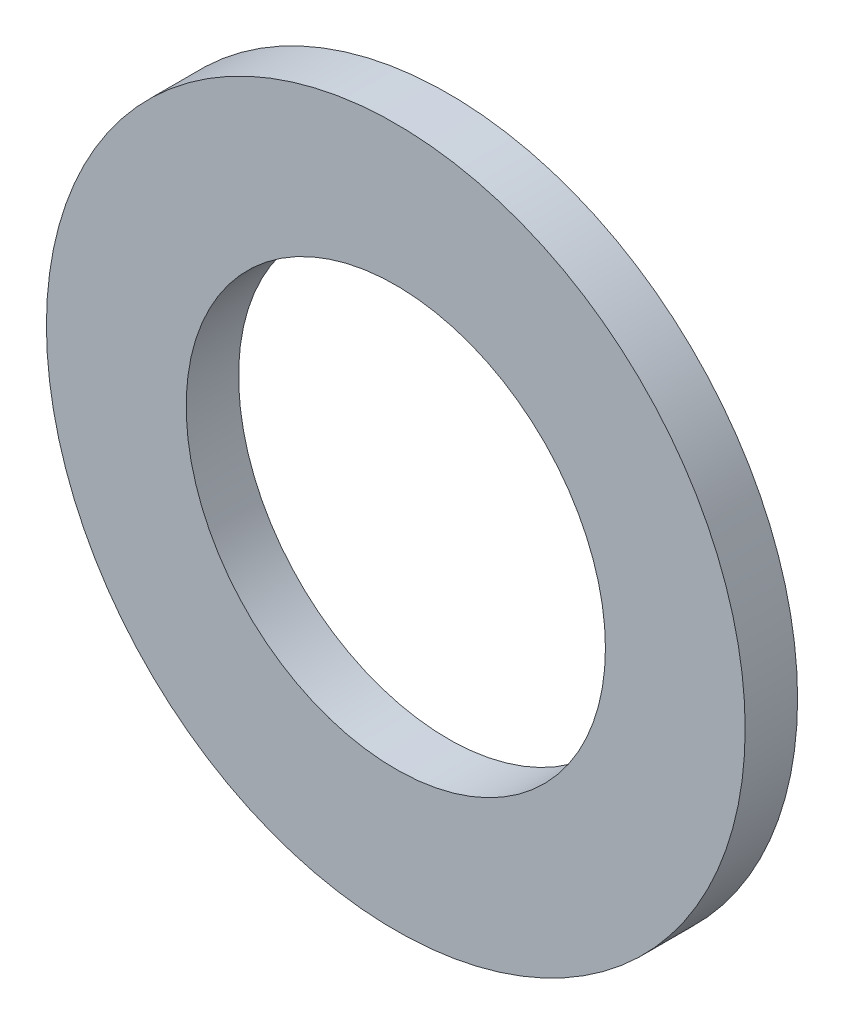
SolidWorks part; units mm, degrees
ref_plane "Front Plane" through (0, 0, 0) normal (0, 0, 1) x (1, 0, 0)
ref_plane "Top Plane" through (0, 0, 0) normal (0, 1, 0) x (1, 0, 0)
ref_plane "Right Plane" through (0, 0, 0) normal (1, 0, 0) x (0, 0, -1)
sketch "Sketch1" plane through (0, 0, 0) normal (0, 0, 1) x (1, 0, 0)
  circle A0 centre (0, 0) radius 6
  circle A1 centre (0, 0) radius 10
  dimension "D1" = 12
  dimension "D2" = 20
extrude "Boss-Extrude1" add sketch "Sketch1" along normal blind 1.5
